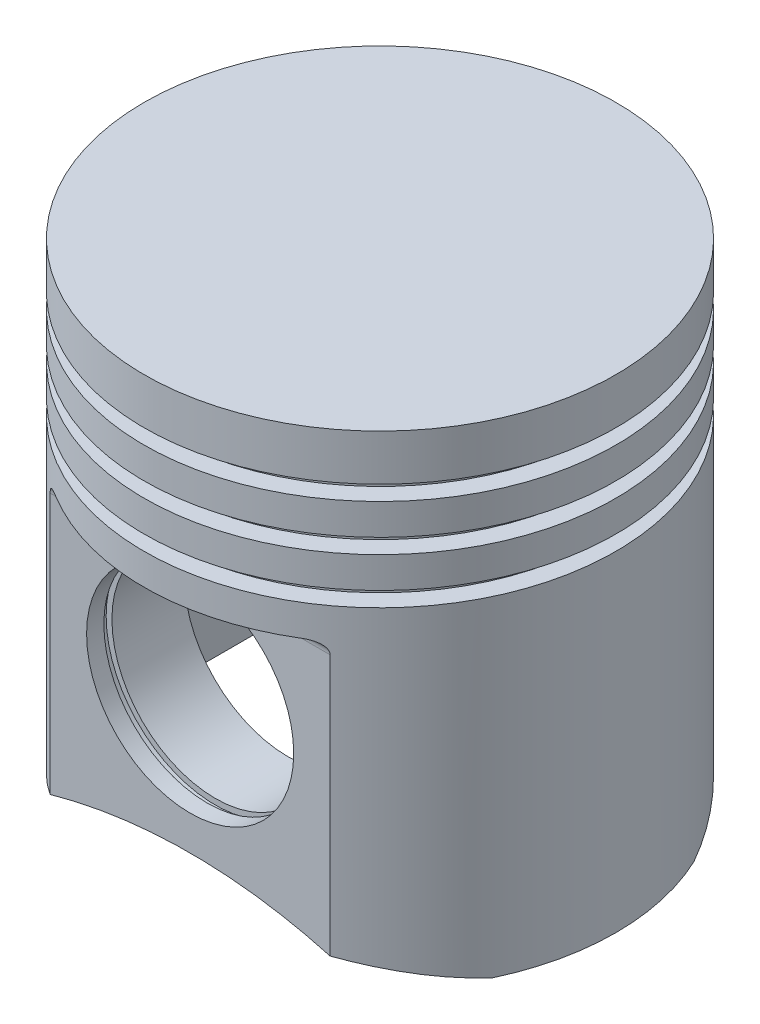
SolidWorks part; units mm, degrees
material "Простая углеродистая сталь"
ref_plane "Front" through (0, 0, 0) normal (0, 0, 1) x (1, 0, 0)
ref_plane "Top" through (0, 0, 0) normal (0, 1, 0) x (1, 0, 0)
ref_plane "Right" through (0, 0, 0) normal (1, 0, 0) x (0, 0, -1)
sketch "Эскиз1" plane through (0, 0, 0) normal (0, 0, 1) x (1, 0, 0)
  line L0 (-132.4031, -93.8656) -> (10.5853, -93.8656) construction
  line L1 (-41, 52) -> (0, 52)
  line L2 (-41, 52) -> (-41, 44)
  line L3 (-41, 44) -> (-37.8, 44)
  line L4 (-37.8, 44) -> (-37.8, 41.4)
  line L5 (-37.8, 41.4) -> (-41, 41.4)
  line L6 (-41, 36) -> (-37.8, 36)
  line L7 (-37.8, 33.4) -> (-41, 33.4)
  line L8 (-41, 28) -> (-37.8, 28)
  line L9 (-37.8, 25.4) -> (-41, 25.4)
  line L10 (-41, 41.4) -> (-41, 36)
  line L11 (-41, 28) -> (-41, 33.4)
  line L12 (-37.8, 33.4) -> (-37.8, 36)
  line L13 (-37.8, 28) -> (-37.8, 25.4)
  line L14 (-41, 25.4) -> (-41, -32)
  line L15 (-41, -32) -> (0, -32)
  line L16 (0, -32) -> (0, 52)
  line L17 (0, 61.035) -> (0, -222.1628) construction
  dimension "D1" = 52
  dimension "D3" = 82
  dimension "D4" = 2.6
  dimension "D5" = 75.6
  dimension "D6" = 8
  dimension "D7" = 16
  dimension "D8" = 84
  dimension "D2" = 3
revolve "Повернуть1" add sketch "Эскиз1" angle 360 about L17
sketch "Эскиз2" plane through (0, 0, 0) normal (0, 0, 1) x (1, 0, 0)
  line L0 (-41, -32) -> (0, -32) construction
  line L1 (-37.0945, -32) -> (37.0945, -32)
  line L2 (41, 52) -> (-41, 52) construction
  arc A0 (-37.0945, -32) -> (37.0945, -32) centre (0, -114) cw
  circle A1 centre (0, 0) radius 18
  dimension "D2" = 76
  dimension "D1" = 90
  dimension "D3" = 36
extrude "Вырез-Вытянуть1" cut sketch "Эскиз2" against normal through all both and the other way through all
sketch "Эскиз3" plane through (0, 0, 0) normal (0, 0, 1) x (1, 0, 0)
  line L0 (-34.1544, -32) -> (-29.7764, 3.6561)
  line L1 (-41, -32) -> (0, -32) construction
  line L4 (0, 61.035) -> (0, -46.4077) construction
  line L5 (0, 61.035) -> (0, -222.1628) construction
  line L6 (34.1544, -32) -> (29.7764, 3.6561)
  line L7 (-34.1544, -32) -> (34.1544, -32)
  arc A0 (-29.7764, 3.6561) -> (29.7764, 3.6561) centre (0, 0) cw
  dimension "D2" = 30
  dimension "D1" = 14
extrude "Вырез-Вытянуть2" cut sketch "Эскиз3" against normal mid plane 32
sketch "Эскиз4" plane through (0, 0, 0) normal (1, 0, 0) x (0, 0, -1)
  line L0 (0, 68.1142) -> (0, -68.5723) construction
  line L1 (0, 61.035) -> (0, -222.1628) construction
  line L2 (41, 52) -> (-41, 52) construction
  line L3 (-41, -32) -> (-33, -32)
  line L4 (-41, -32) -> (-41, 20)
  line L5 (-41, 20) -> (-35, 20)
  line L6 (-33, -32) -> (-33, 18)
  line L7 (-17.4642, -32) -> (17.4642, -32) construction
  line L8 (-41, 52) -> (-41, 44) construction
  line L9 (33, -32) -> (33, 18)
  line L10 (41, 20) -> (35, 20)
  line L11 (41, -32) -> (41, 20)
  line L12 (41, -32) -> (33, -32)
  arc A0 (33, 18) -> (35, 20) centre (35, 18) cw
  arc A1 (-35, 20) -> (-33, 18) centre (-35, 18) cw
  point P20 (33, 20)
  point P23 (-33, 20)
  dimension "D3" = 2
  dimension "D1" = 32
  dimension "D2" = 66
extrude "Вырез-Вытянуть3" cut sketch "Эскиз4" against normal through all both and the other way through all
sketch "Эскиз5" plane through (0, 0, 0) normal (1, 0, 0) x (0, 0, -1)
  line L0 (-40.792, 0) -> (47.1091, 0) construction
  line L1 (16, -18) -> (33, -18) construction
  line L2 (30, -18) -> (28.6, -18)
  line L3 (30, -18) -> (30, -19)
  line L4 (30, -19) -> (28.6, -19)
  line L5 (28.6, -18) -> (28.6, -19)
  line L6 (0, 0) -> (0, -38.3139) construction
  line L7 (-28.6, -18) -> (-28.6, -19)
  line L8 (-30, -19) -> (-28.6, -19)
  line L9 (-30, -18) -> (-30, -19)
  line L10 (-30, -18) -> (-28.6, -18)
  line L12 (-33, 18) -> (-33, -18) construction
  dimension "D1" = 3
  dimension "D2" = 1.4
  dimension "D3" = 38
revolve "Вырез-Повернуть1" cut sketch "Эскиз5" angle 360 about L0
